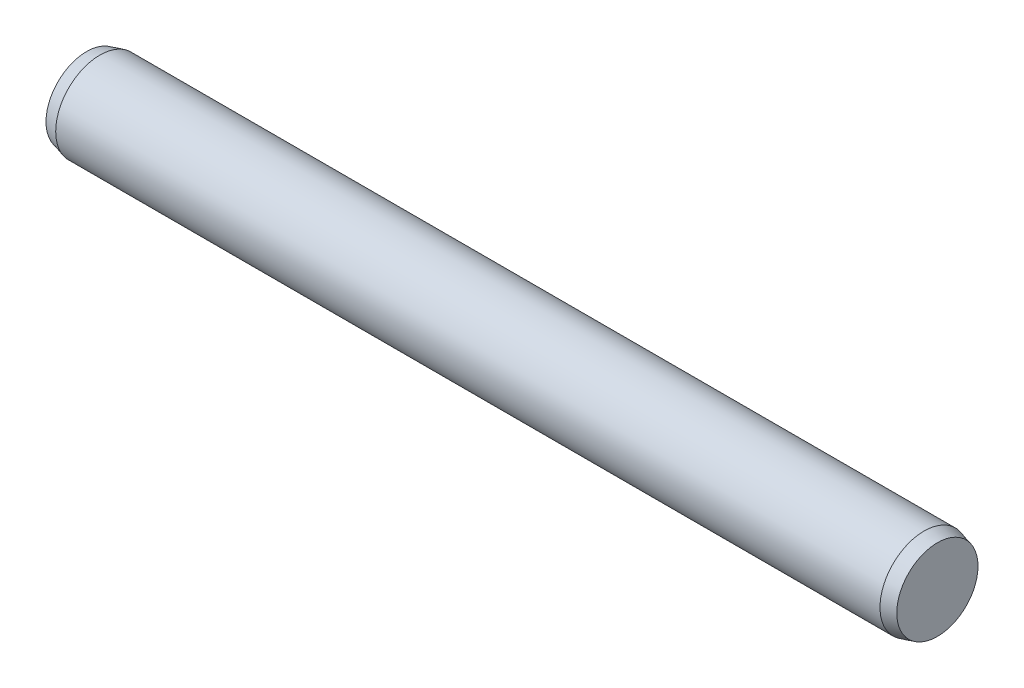
SolidWorks part; units mm, degrees
ref_plane "Front Plane" through (0, 0, 0) normal (0, 0, 1) x (1, 0, 0)
ref_plane "Top Plane" through (0, 0, 0) normal (0, 1, 0) x (1, 0, 0)
ref_plane "Right Plane" through (0, 0, 0) normal (1, 0, 0) x (0, 0, -1)
sketch "Sketch1" plane through (0, 0, 0) normal (0, 0, 1) x (1, 0, 0)
  line L0 (-14, 0) -> (14, 0) construction
  line L1 (14, 1.5) -> (14, -1.5) construction
  line L2 (-14, 1.5) -> (-14, -1.5) construction
  line L3 (14.45, 1.5) -> (14.45, -1.5) construction
  line L4 (-14.45, 1.5) -> (-14.45, -1.5) construction
  line L5 (-14, 0) -> (-14.45, 0) construction
  line L6 (14, 0) -> (14.45, 0) construction
  dimension "D1" = 0.45
  dimension "Dia" = 3
  dimension "Length" = 28
  dimension "C" = 0.45
sketch "Sketch2" plane through (0, 0, 0) normal (1, 0, 0) x (0, 0, -1)
  circle A0 centre (0, 0) radius 1.5
extrude "Extrude1" add sketch "Sketch2" against normal up to vertex (14 mm away) and the other way up to vertex (14 mm away) up to point (-14, 1.5, 0) other way up to point (14, 1.5, 0)
sketch "Sketch3" plane through (14, 0, 0) normal (1, 0, 0) x (0, 0, -1)
  circle A1 centre (0, 0) radius 1.5
  circle A2 centre (0, 0) radius 1.5
  dimension "D1" = 0
extrude "Extrude2" add sketch "Sketch3" along normal up to vertex (0.45 mm away) draft 15 up to point (14.45, 0, 0)
sketch "Sketch4" plane through (-14, 0, 0) normal (-1, 0, 0) x (0, 0, 1)
  circle A1 centre (0, 0) radius 1.5
  circle A2 centre (0, 0) radius 1.5
  dimension "D1" = 0
extrude "Extrude3" add sketch "Sketch4" along normal up to vertex (0.45 mm away) draft 15 up to point (-14.45, 0, 0)
equation "\"D1@Sketch1\" = \"C@Sketch1\""
